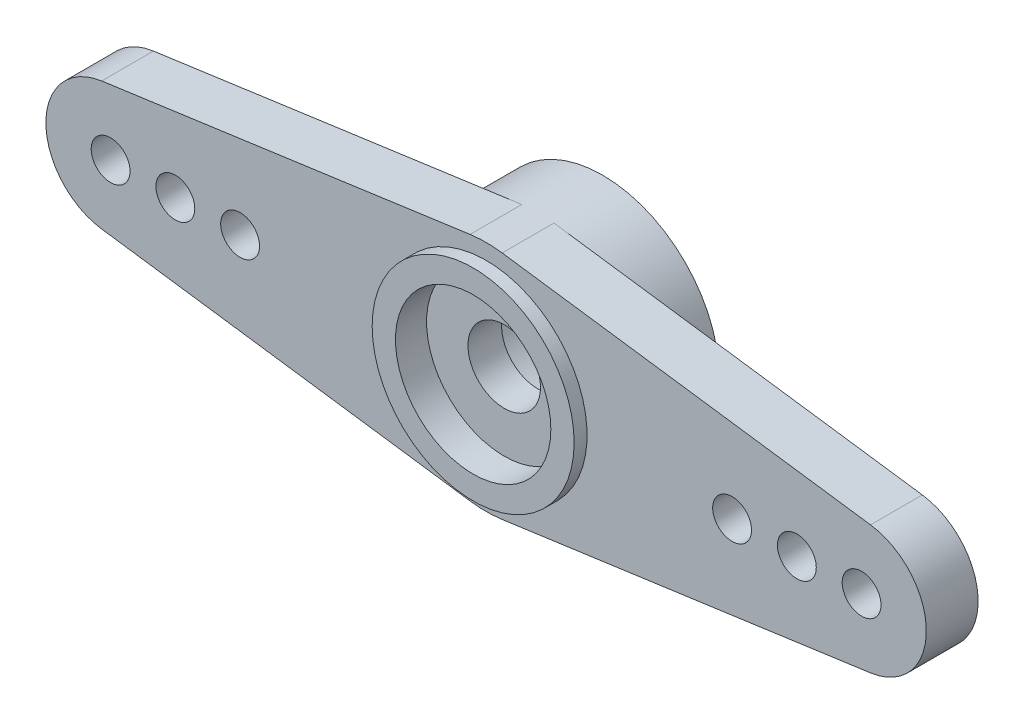
SolidWorks part; units mm, degrees
ref_plane "Plan de face" through (0, 0, 0) normal (0, 0, 1) x (1, 0, 0)
ref_plane "Plan de dessus" through (0, 0, 0) normal (0, 1, 0) x (1, 0, 0)
ref_plane "Plan de droite" through (0, 0, 0) normal (1, 0, 0) x (0, 0, -1)
sketch "Esquisse1" plane through (0, 0, 0) normal (0, 0, 1) x (1, 0, 0)
  line L0 (-21.012, 0) -> (24.7162, 0) construction
  line L1 (0, 12.6167) -> (0, -11.3136) construction
  line L2 (17, 3.6132) -> (17, -5.2718) construction
  line L3 (-17, 3.6132) -> (-17, -5.2718) construction
  line L4 (4.3399, 4.5) -> (-5.2559, 4.5) construction
  line L5 (-5.2559, -4.5) -> (4.3399, -4.5) construction
  line L6 (-0.6207, 4.457) -> (-14.8448, 2.4761)
  line L7 (-14.8448, -2.4761) -> (-0.6207, -4.457)
  line L8 (0.6207, -4.457) -> (14.8448, -2.4761)
  line L9 (14.8448, 2.4761) -> (0.6207, 4.457)
  circle A0 centre (-14.5, 0) radius 2.5 construction
  circle A1 centre (14.5, 0) radius 2.5 construction
  circle A2 centre (0, 0) radius 4.5 construction
  arc A3 (-14.8448, 2.4761) -> (-14.8448, -2.4761) centre (-14.5, 0) ccw
  arc A4 (14.8448, 2.4761) -> (14.8448, -2.4761) centre (14.5, 0) cw
  arc A5 (0.6207, -4.457) -> (-0.6207, -4.457) centre (0, 0) cw
  arc A6 (-0.6207, 4.457) -> (0.6207, 4.457) centre (0, 0) cw
  circle A7 centre (0, 0) radius 1.4
  circle A8 centre (14.5, 0) radius 0.75
  circle A9 centre (-14.5, 0) radius 0.75
  circle A10 centre (-12, 0) radius 0.75
  circle A11 centre (-9.5, 0) radius 0.75
  circle A12 centre (9.5, 0) radius 0.75
  circle A13 centre (12, 0) radius 0.75
  dimension "D4" = 5
  dimension "D6" = 2.8
  dimension "D7" = 1.5
  dimension "D8" = 1.5
  dimension "D9" = 2.5
  dimension "D1" = 34
  dimension "D2" = 4.5
  dimension "D3" = 4.5
  dimension "D5" = 17
  dimension "D10" = 2.5
  dimension "D11" = 2.5
  dimension "D12" = 2.5
extrude "Boss.-Extru.1" add sketch "Esquisse1" along normal blind 2
sketch "Esquisse2" plane through (0, 0, 2) normal (0, 0, 1) x (1, 0, 0)
  circle A0 centre (0, 0) radius 3.9
  circle A1 centre (0, 0) radius 3
  dimension "D1" = 7.8
  dimension "D2" = 6
extrude "Boss.-Extru.2" add sketch "Esquisse2" along normal blind 0.5
sketch "Esquisse3" plane through (0, 0, 2.5) normal (0, 0, 1) x (1, 0, 0)
  circle A0 centre (0, 0) radius 3
extrude "Enlèv. mat.-Extru.1" cut sketch "Esquisse3" against normal blind 1.2
sketch "Esquisse4" plane through (0, 0, 0) normal (0, 0, -1) x (-1, 0, 0)
  circle A0 centre (0, 0) radius 4.5
  circle A1 centre (0, 0) radius 2.75
  dimension "D1" = 5.5
  dimension "D2" = 9
extrude "Boss.-Extru.3" add sketch "Esquisse4" along normal blind 2.5
